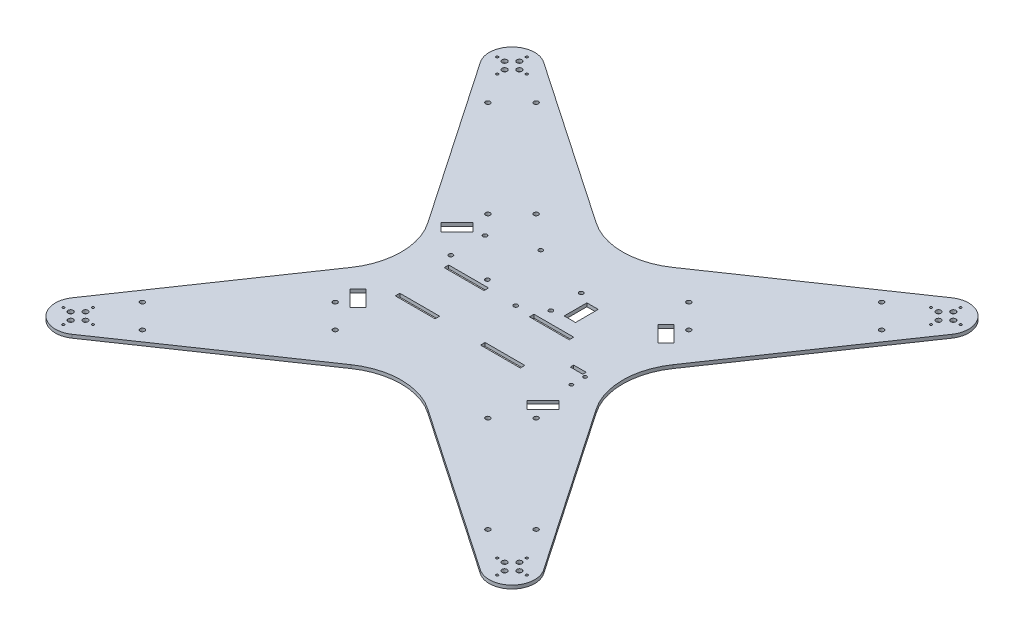
SolidWorks part; units mm, degrees
ref_plane "Front Plane" through (0, 0, 0) normal (0, 0, 1) x (1, 0, 0)
ref_plane "Top Plane" through (0, 0, 0) normal (0, 1, 0) x (1, 0, 0)
ref_plane "Right Plane" through (0, 0, 0) normal (1, 0, 0) x (0, 0, -1)
sketch "Sketch1" plane through (0, 0, 0) normal (0, 1, 0) x (1, 0, 0)
  line L0 (84.8528, 0) -> (0, 84.8528) construction
  line L1 (0, 84.8528) -> (179.6458, 207.4391)
  line L2 (42.4264, 42.4264) -> (190.9188, 190.9188) construction
  line L3 (207.4391, 179.6458) -> (84.8528, 0)
  line L4 (0, 84.8528) -> (0, 0)
  line L5 (0, 0) -> (84.8528, 0)
  line L6 (42.4264, 42.4264) -> (0, 0) construction
  line L7 (197.4188, 190.9188) -> (190.9188, 184.4188) construction
  line L8 (197.4188, 190.9188) -> (190.9188, 197.4188) construction
  line L9 (190.9188, 184.4188) -> (184.4188, 190.9188) construction
  line L10 (190.9188, 197.4188) -> (184.4188, 190.9188) construction
  line L11 (197.4188, 190.9188) -> (184.4188, 190.9188) construction
  line L12 (190.9188, 184.4188) -> (190.9188, 197.4188) construction
  line L13 (203.9188, 190.9188) -> (190.9188, 177.9188) construction
  line L14 (203.9188, 190.9188) -> (190.9188, 203.9188) construction
  line L15 (190.9188, 177.9188) -> (177.9188, 190.9188) construction
  line L16 (190.9188, 203.9188) -> (177.9188, 190.9188) construction
  line L17 (203.9188, 190.9188) -> (177.9188, 190.9188) construction
  line L18 (190.9188, 177.9188) -> (190.9188, 203.9188) construction
  line L19 (173.2412, 152.028) -> (152.028, 173.2412) construction
  line L20 (0, 0) -> (200, 0) construction
  line L21 (77.7817, 77.7817) -> (67.1751, 88.3883) construction
  line L22 (77.7817, 77.7817) -> (88.3883, 67.1751) construction
  arc A0 (179.6458, 207.4391) -> (207.4391, 179.6458) centre (190.9188, 190.9188) cw
  circle A1 centre (177.9188, 190.9188) radius 1
  circle A2 centre (190.9188, 203.9188) radius 1
  circle A3 centre (203.9188, 190.9188) radius 1
  circle A4 centre (197.4188, 190.9188) radius 2.25
  circle A5 centre (190.9188, 197.4188) radius 2.25
  circle A6 centre (184.4188, 190.9188) radius 2.25
  circle A7 centre (190.9188, 184.4188) radius 2.25
  circle A8 centre (190.9188, 177.9188) radius 1
  circle A9 centre (152.028, 173.2412) radius 2
  circle A10 centre (173.2412, 152.028) radius 2
  circle A11 centre (67.1751, 88.3883) radius 2
  circle A12 centre (88.3883, 67.1751) radius 2
  point P28 (162.6346, 162.6346)
  dimension "D3" = 20
  dimension "D7" = 2
  dimension "D8" = 2
  dimension "D9" = 4.5
  dimension "D10" = 4.5
  dimension "D11" = 4.5
  dimension "D12" = 2
  dimension "D13" = 4.5
  dimension "D14" = 2
  dimension "D15" = 4
  dimension "D16" = 4
  dimension "D21" = 4
  dimension "D22" = 4
  dimension "D1" = 210
  dimension "D2" = 120
  dimension "D4" = 60
  dimension "D5" = 26
  dimension "D6" = 13
  dimension "D17" = 30
  dimension "D18" = 40
  dimension "D19" = 200
  dimension "D20" = 45
  dimension "D23" = 30
  dimension "D24" = 120
extrude "Boss-Extrude1" add sketch "Sketch1" along normal blind 3
pattern_circular "CirPattern1" count 4 over 360 about axis through (0, 0, 0) along (0, 1, 0) of "Boss-Extrude1"
sketch "Sketch2" plane through (0, 3, 0) normal (0, 1, 0) x (1, 0, 0)
  line L0 (78.5365, -14.2236) -> (78.5012, -26.2236) construction
  line L1 (78.5012, -26.2236) -> (12.8814, 21.2788) construction
  line L2 (12.8814, 21.2788) -> (12.8814, 48.0179) construction
  line L3 (12.8814, 48.0179) -> (-38.4858, 16.8899) construction
  line L4 (-38.4858, 16.8899) -> (-37.5695, 62.8272) construction
  line L5 (-37.5695, 62.8272) -> (12.8814, 21.2788) construction
  line L6 (12.8814, 21.2788) -> (-38.4858, 16.8899) construction
  line L7 (-38.4858, 16.8899) -> (-73.2421, 49.4521) construction
  line L8 (-73.2421, 49.4521) -> (-37.5695, 62.8272) construction
  line L9 (-37.5695, 62.8272) -> (12.8814, 48.0179) construction
  line L10 (12.8814, 48.0179) -> (78.5365, -14.2236) construction
  line L11 (-66.7313, 7.059) -> (-66.7313, -31.9732) construction
  line L12 (-66.7313, 11.059) -> (-31.7313, 11.059)
  line L13 (-66.7313, 11.059) -> (-66.7313, 7.059)
  line L14 (-66.7313, 7.059) -> (-31.7313, 7.059)
  line L15 (-31.7313, 11.059) -> (-31.7313, 7.059)
  line L16 (43.2687, 11.059) -> (8.2687, 11.059)
  line L17 (43.2687, 11.059) -> (43.2687, 7.059)
  line L18 (43.2687, 7.059) -> (8.2687, 7.059)
  line L19 (8.2687, 11.059) -> (8.2687, 7.059)
  line L20 (-66.7313, -31.9732) -> (-31.7313, -31.9732)
  line L21 (-66.7313, -31.9732) -> (-66.7313, -35.9732)
  line L22 (-66.7313, -35.9732) -> (-31.7313, -35.9732)
  line L23 (-31.7313, -31.9732) -> (-31.7313, -35.9732)
  line L24 (8.2687, -31.9732) -> (43.2687, -31.9732)
  line L25 (8.2687, -31.9732) -> (8.2687, -35.9732)
  line L26 (8.2687, -35.9732) -> (43.2687, -35.9732)
  line L27 (43.2687, -31.9732) -> (43.2687, -35.9732)
  line L28 (8.2687, -31.9732) -> (8.2687, 7.059) construction
  line L29 (-31.7313, 7.059) -> (8.2687, 7.059) construction
  line L30 (-31.7313, -31.9732) -> (8.2687, -31.9732) construction
  line L31 (-73.2421, 49.4521) -> (-73.2421, 19.4521) construction
  circle A0 centre (78.5365, -14.2236) radius 1.5
  circle A1 centre (78.5012, -26.2236) radius 1.5
  circle A2 centre (12.8814, 21.2788) radius 1.8
  circle A3 centre (12.8814, 48.0179) radius 1.8
  circle A4 centre (-38.4858, 16.8899) radius 1.8
  circle A5 centre (-37.5695, 62.8272) radius 1.8
  circle A6 centre (-73.2421, 49.4521) radius 1.8
  circle A7 centre (-6.3066, 9.5674) radius 1.8
  circle A8 centre (-73.2421, 19.4521) radius 1.8
  dimension "D1" = 3
  dimension "D2" = 3
  dimension "D3" = 12
  dimension "D5" = 3.6
  dimension "D6" = 3.6
  dimension "D7" = 3.6
  dimension "D8" = 3.6
  dimension "D9" = 3.6
  dimension "D14" = 3.6
  dimension "D29" = 3.6
  dimension "D4" = 4.3889
  dimension "D10" = 51.3673
  dimension "D11" = 26.7391
  dimension "D12" = 50.451
  dimension "D13" = 14.8093
  dimension "D15" = 35
  dimension "D16" = 35
  dimension "D17" = 35
  dimension "D18" = 65.6197
  dimension "D19" = 47.5024
  dimension "D20" = 62.2416
  dimension "D21" = 65.6551
  dimension "D22" = 35
  dimension "D23" = 39.0322
  dimension "D24" = 4
  dimension "D25" = 4
  dimension "D26" = 4
  dimension "D27" = 4
  dimension "D28" = 40
  dimension "D30" = 30
extrude "Cut-Extrude1" cut sketch "Sketch2" against normal through all
sketch "Sketch4" plane through (0, 3, 0) normal (0, 1, 0) x (1, 0, 0)
  line L0 (210.9188, 210.9188) -> (210.9188, -210.9188)
  line L1 (210.9188, 210.9188) -> (-210.9188, 210.9188)
  line L2 (210.9188, -210.9188) -> (-210.9188, -210.9188)
  line L3 (-210.9188, 210.9188) -> (-210.9188, -210.9188)
  line L4 (210.9188, 210.9188) -> (-210.9188, -210.9188) construction
  line L5 (210.9188, -210.9188) -> (-210.9188, 210.9188) construction
  arc A0 (207.4391, 179.6458) -> (179.6458, 207.4391) centre (190.9188, 190.9188) ccw construction
  arc A1 (-179.6458, 207.4391) -> (-207.4391, 179.6458) centre (-190.9188, 190.9188) ccw construction
  point P1 (0, 0)
  point P4 (210.9188, 0)
  dimension "D1" = 421.8377
fillet "Fillet1" radius 60 4 edges at (0, 1.5, -84.8528) (0, 1.5, 84.8528) (84.8528, 1.5, 0) (-84.8528, 1.5, 0)
sketch "Sketch6" plane through (0, 0, 0) normal (0, -1, 0) x (1, 0, 0)
  line L0 (-91.9239, 50.6396) -> (-77.7817, 64.7817)
  line L1 (-91.9239, 50.6396) -> (-84.8528, 43.5685)
  line L2 (-77.7817, 64.7817) -> (-70.7107, 57.7107)
  line L3 (-84.8528, 43.5685) -> (-70.7107, 57.7107)
  line L4 (-190.9188, 177.9188) -> (-77.7817, 64.7817) construction
  line L5 (-190.9188, 177.9188) -> (-177.9188, 190.9188) construction
  line L6 (-102.5305, -40.033) -> (-95.4594, -32.9619)
  line L7 (-102.5305, -40.033) -> (-88.3883, -54.1751)
  line L8 (-95.4594, -32.9619) -> (-81.3173, -47.1041)
  line L9 (-88.3883, -54.1751) -> (-81.3173, -47.1041)
  line L10 (77.7817, -64.7817) -> (70.7107, -57.7107)
  line L11 (77.7817, -64.7817) -> (91.9239, -50.6396)
  line L12 (70.7107, -57.7107) -> (84.8528, -43.5685)
  line L13 (91.9239, -50.6396) -> (84.8528, -43.5685)
  line L14 (84.8528, 43.5685) -> (70.7107, 57.7107)
  line L15 (84.8528, 43.5685) -> (91.9239, 50.6396)
  line L16 (70.7107, 57.7107) -> (77.7817, 64.7817)
  line L17 (91.9239, 50.6396) -> (77.7817, 64.7817)
  line L18 (190.9188, 177.9188) -> (177.9188, 190.9188) construction
  line L19 (190.9188, 177.9188) -> (77.7817, 64.7817) construction
  line L20 (190.9188, -177.9188) -> (177.9188, -190.9188) construction
  line L21 (77.7817, -64.7817) -> (190.9188, -177.9188) construction
  line L22 (-177.9188, -190.9188) -> (-190.9188, -177.9188) construction
  line L23 (-190.9188, -177.9188) -> (-77.7817, -64.7817) construction
  line L24 (22.8814, -23.0179) -> (22.8814, -43.0179)
  line L25 (22.8814, -23.0179) -> (32.8814, -23.0179)
  line L26 (22.8814, -43.0179) -> (32.8814, -43.0179)
  line L27 (32.8814, -23.0179) -> (32.8814, -43.0179)
  line L28 (-77.7817, -64.7817) -> (-88.3883, -54.1751) construction
  circle A0 centre (12.8814, -21.2788) radius 1.8 construction
  circle A1 centre (-190.9188, 177.9188) radius 1 construction
  circle A2 centre (12.8814, -48.0179) radius 1.8 construction
  dimension "D3" = 160
  dimension "D4" = 20
  dimension "D15" = 10
  dimension "D16" = 5
  dimension "D1" = 10
  dimension "D2" = 20
  dimension "D5" = 20
  dimension "D6" = 20
  dimension "D7" = 10
  dimension "D8" = 10
  dimension "D9" = 10
  dimension "D10" = 160
  dimension "D11" = 15
  dimension "D12" = 160
  dimension "D13" = 20
  dimension "D14" = 10
  dimension "D17" = 160
extrude "Cut-Extrude2" cut sketch "Sketch6" against normal blind 10
sketch "Sketch7" plane through (0, 3, 0) normal (0, 1, 0) x (1, 0, 0)
  line L1 (64.5365, -10.2236) -> (75.5365, -10.2236)
  line L2 (64.5365, -10.2236) -> (64.5365, -13.2236)
  line L3 (64.5365, -13.2236) -> (75.5365, -13.2236)
  line L4 (75.5365, -10.2236) -> (75.5365, -13.2236)
  circle A0 centre (78.5365, -14.2236) radius 1.5 construction
  dimension "D1" = 11
  dimension "D2" = 3
  dimension "D3" = 3
  dimension "D4" = 1
extrude "Cut-Extrude3" cut sketch "Sketch7" against normal through all
equation "\"D4@Sketch1\"=\"D2@Sketch1\"/2"
equation "\"D8@Sketch1\"=\"D7@Sketch1\""
equation "\"D9@Sketch1\"=\"D10@Sketch1\""
equation "\"D11@Sketch1\"=\"D10@Sketch1\""
equation "\"D12@Sketch1\"=\"D7@Sketch1\""
equation "\"D13@Sketch1\"=\"D10@Sketch1\""
equation "\"D14@Sketch1\"=\"D7@Sketch1\""
equation "\"D21@Sketch1\"=\"D16@Sketch1\""
equation "\"D22@Sketch1\"=\"D16@Sketch1\""
